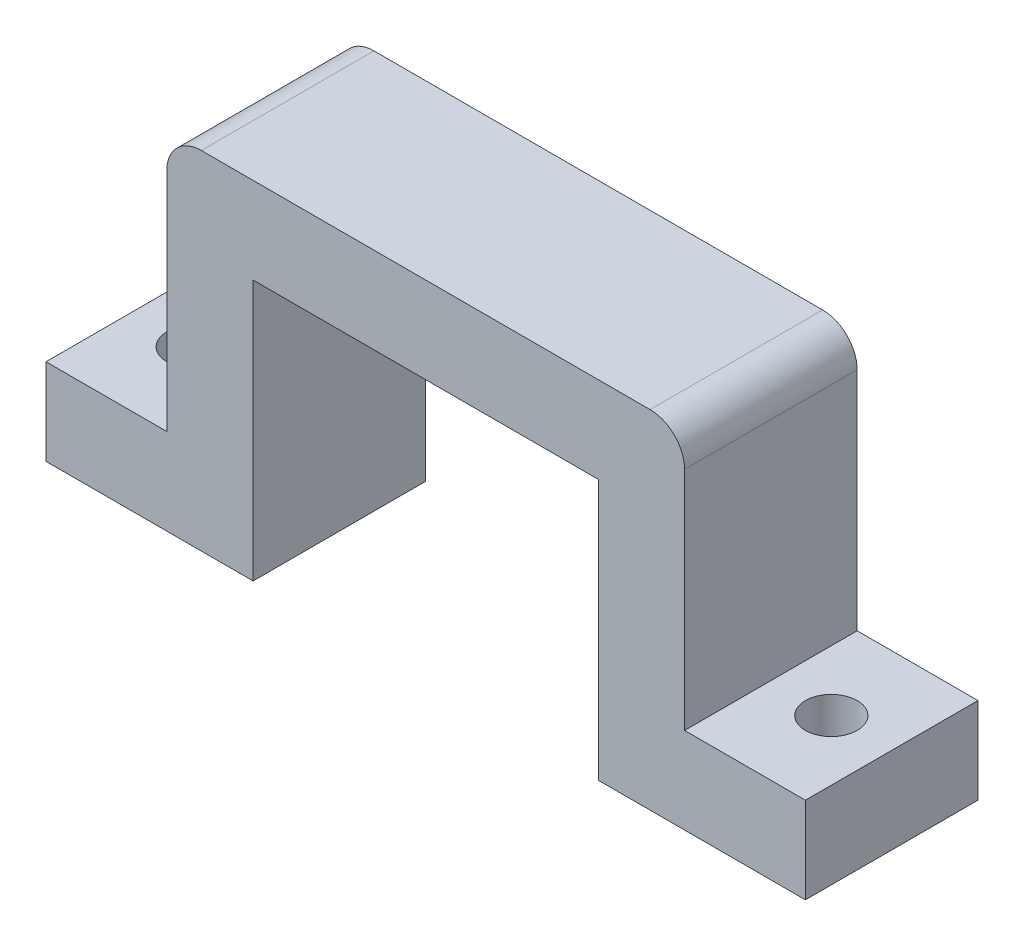
SolidWorks part; units mm, degrees
ref_plane "Plan de face" through (0, 0, 0) normal (0, 0, 1) x (1, 0, 0)
ref_plane "Plan de dessus" through (0, 0, 0) normal (0, 1, 0) x (1, 0, 0)
ref_plane "Plan de droite" through (0, 0, 0) normal (1, 0, 0) x (0, 0, -1)
sketch "Esquisse1" plane through (0, 0, 0) normal (0, 0, 1) x (1, 0, 0)
  line L0 (0, 0) -> (0, 15.1)
  line L1 (0, 15.1) -> (20, 15.1)
  line L2 (20, 15.1) -> (20, 0)
  line L3 (10, 16.8337) -> (10, -3.3499) construction
  line L4 (0, 0) -> (-12, 0)
  line L5 (20, 0) -> (32, 0)
  line L6 (-5, 5) -> (-12, 5)
  line L7 (-5, 5) -> (-5, 18.1)
  line L8 (-3, 20.1) -> (23, 20.1)
  line L9 (25, 18.1) -> (25, 5)
  line L10 (25, 5) -> (32, 5)
  line L11 (-12, 5) -> (-12, 0)
  line L12 (32, 5) -> (32, 0)
  line L13 (-5, 20.1) -> (25, 20.1) construction
  line L14 (25, 20.1) -> (25, 5) construction
  line L15 (-5, 5) -> (-5, 20.1) construction
  arc A0 (23, 20.1) -> (25, 18.1) centre (23, 18.1) cw
  arc A1 (-5, 18.1) -> (-3, 20.1) centre (-3, 18.1) cw
  dimension "D5" = 2
  dimension "D1" = 15.1
  dimension "D2" = 20
  dimension "D3" = 12
  dimension "D4" = 5
extrude "Boss.-Extru.1" add sketch "Esquisse1" along normal blind 10
sketch "Esquisse2" plane through (0, 5, 0) normal (0, 1, 0) x (1, 0, 0)
  line L0 (10, 5.3507) -> (10, -16.6558) construction
  line L1 (-12, -10) -> (-12, 0) construction
  circle A0 centre (-8.5, -5) radius 1.5
  circle A1 centre (28.5, -5) radius 1.5
  dimension "D1" = 3
  dimension "D2" = 3.5
extrude "Enlèv. mat.-Extru.1" cut sketch "Esquisse2" against normal blind 10
